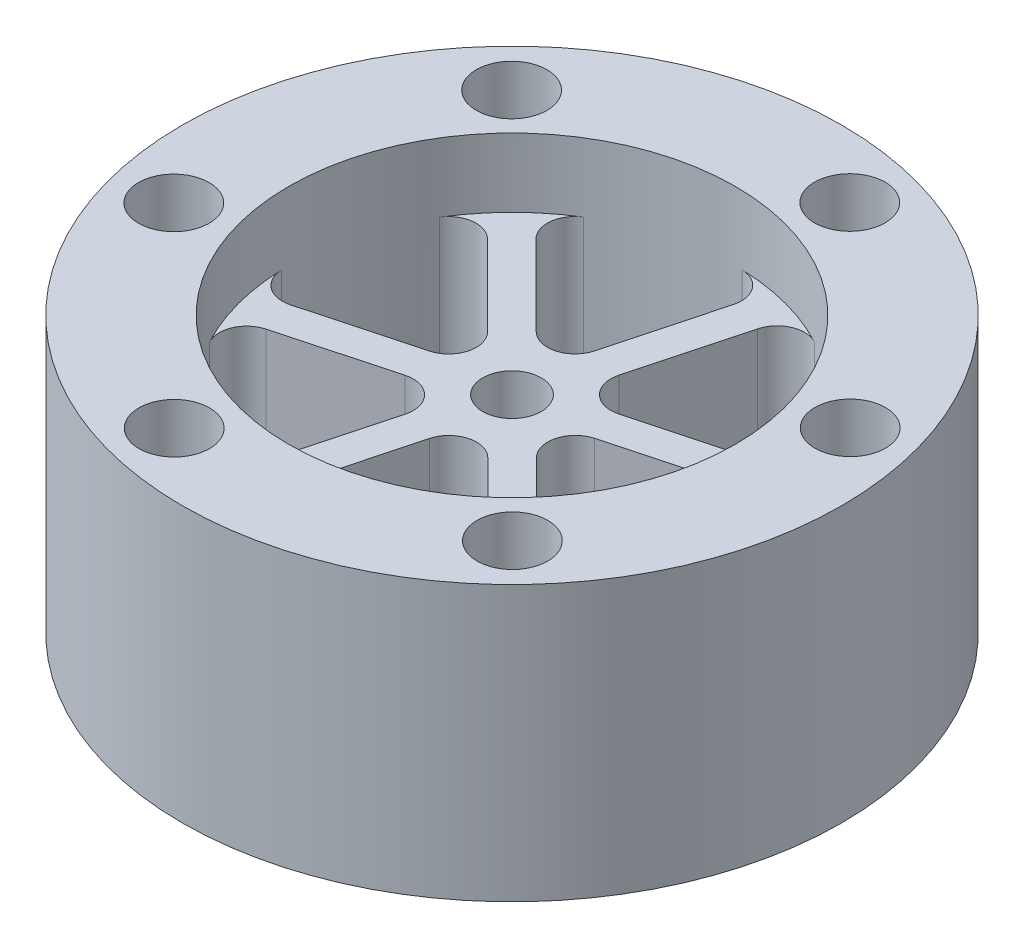
SolidWorks part; units mm, degrees
material "AISI 316 Stainless Steel Sheet (SS)"
ref_plane "Front Plane" through (0, 0, 0) normal (0, 0, 1) x (1, 0, 0)
ref_plane "Top Plane" through (0, 0, 0) normal (0, 1, 0) x (1, 0, 0)
ref_plane "Right Plane" through (0, 0, 0) normal (1, 0, 0) x (0, 0, -1)
sketch "Sketch1" plane through (0, 0, 0) normal (0, 1, 0) x (1, 0, 0)
  circle A0 centre (0, 0) radius 30.48
  dimension "D1" = 60.96
extrude "Boss-Extrude1" add sketch "Sketch1" along normal blind 25.4
hole_wizard "1/4-28 Tapped Hole1" positions "Sketch3" profile "Sketch4" tap size "1/4-28" standard "ANSI Inch" end condition through all
sketch "Sketch3" plane through (0, 25.4, 0) normal (0, 1, 0) x (1, 0, 0)
  point P0 (0, 0)
sketch "Sketch4" plane through (0, 25.4, 0) normal (1, 0, 0) x (0, 0, 1)
  line L0 (0, 0) -> (0, 25.4)
  line L1 (0, 25.4) -> (2.7051, 25.4)
  line L2 (2.7051, 25.4) -> (2.7051, 0)
  line L5 (2.7051, 0) -> (0, 0)
  line L11 (0, -6.35) -> (0, 107.95) construction
  dimension "Thru Tap Drill Dia." = 5.4102
  dimension "Thru Tap Drill Depth" = 25.4
cosmetic thread "Hole Thread1" parameters "D2"=6.35
hole_wizard "1/4 Clearance Hole2" positions "Sketch6" profile "Sketch5" hole size "1/4" standard "ANSI Inch" end condition through all
sketch "Sketch6" plane through (0, 0, 0) normal (0, -1, 0) x (-1, 0, 0)
  point P0 (269.1744, -128.7729)
  point P1 (-18.0582, -18.0219)
  point P4 (6.5783, -24.6498)
  point P7 (-24.6365, 6.6279)
  point P10 (-6.5783, 24.6498)
  point P13 (18.0582, 18.0219)
  point P16 (24.6365, -6.6279)
sketch "Sketch5" plane through (-269.1744, 0, 128.7729) normal (1, 0, 0) x (0, 0, -1)
  line L0 (0, 0) -> (0, 25.4)
  line L1 (0, 25.4) -> (3.2639, 25.4)
  line L2 (3.2639, 25.4) -> (3.2639, 0)
  line L5 (3.2639, 0) -> (0, 0)
  line L11 (0, -6.35) -> (0, 107.95) construction
  dimension "Thru Hole Dia." = 6.5278
  dimension "Thru Hole Depth" = 25.4
sketch "Sketch7" plane through (0, 25.4, 0) normal (0, 1, 0) x (1, 0, 0)
  line L0 (0, 0) -> (6.5783, 24.6498) construction
  line L2 (0, 0) -> (-18.0582, 18.0219) construction
  line L3 (-13.4519, 15.6677) -> (-0.8248, 3.066)
  line L4 (-0.8248, 3.066) -> (3.775, 20.3022)
  arc A0 (3.775, 20.3022) -> (-13.4519, 15.6677) centre (0, 0) ccw
  dimension "D3" = 20.6502
  dimension "D1" = 3.175
  dimension "D2" = 3.175
extrude "Cut-Extrude1" cut sketch "Sketch7" against normal through all
fillet "Fillet1" radius 2.54 3 edges at (-0.8248, 12.7, -3.066) (-13.4519, 12.7, -15.6677) (3.775, 12.7, -20.3022)
pattern_circular "CirPattern1" count 6 over 360 about axis through (0, 0, 0) along (0, 1, 0) of "Cut-Extrude1", "Fillet1"
sketch "Sketch8" plane through (0, 25.4, 0) normal (0, -1, 0) x (1, 0, 0)
  circle A0 centre (0, 0) radius 20.6502
  arc A1 (20.639, -0.6787) -> (17.5565, 10.872) centre (0, 0) ccw construction
extrude "Cut-Extrude2" cut sketch "Sketch8" along normal blind 6.35
